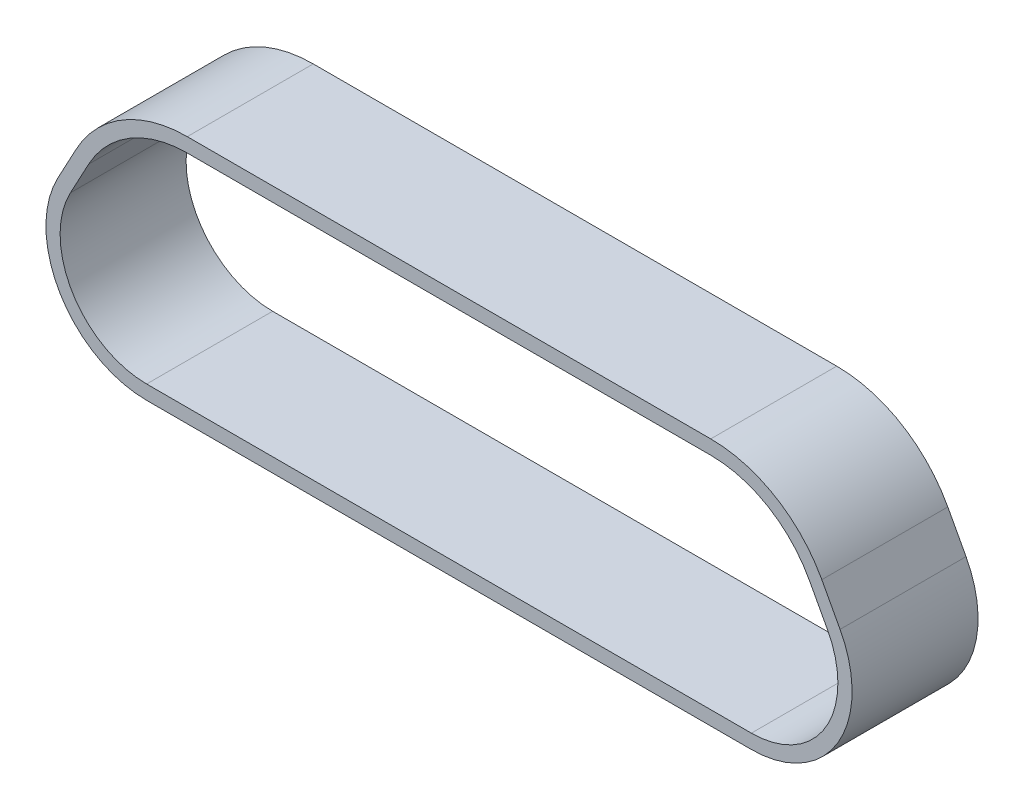
SolidWorks part; units mm, degrees
material "ﾎﾟﾘｳﾚﾀﾝ(POLYURETHANE) (11671)"
ref_plane "正面" through (0, 0, 0) normal (0, 0, 1) x (1, 0, 0)
ref_plane "平面" through (0, 0, 0) normal (0, 1, 0) x (1, 0, 0)
ref_plane "右側面" through (0, 0, 0) normal (1, 0, 0) x (0, 0, -1)
sketch "ｽｹｯﾁ1" plane through (0, 0, 0) normal (0, 0, 1) x (1, 0, 0)
  line L0 (-96, 0) -> (96, 0) construction
  line L2 (-96, -31.83) -> (96, -31.83)
  line L5 (-124.0339, 15.0747) -> (-118.2415, 25.8467)
  line L6 (-83.1, 46.85) -> (83.1, 46.85)
  line L7 (118.2415, 25.8467) -> (124.0339, 15.0747)
  line L8 (121.2536, 27.4664) -> (127.0461, 16.6945) construction
  line L9 (-96, -35.25) -> (96, -35.25) construction
  line L10 (-127.0461, 16.6945) -> (-121.2536, 27.4664) construction
  line L11 (-83.1, 50.27) -> (83.1, 50.27) construction
  line L12 (118.171, 25.8088) -> (123.9635, 15.0369) construction
  line L13 (-96, -31.75) -> (96, -31.75) construction
  line L14 (-123.9635, 15.0369) -> (-118.171, 25.8088) construction
  line L15 (-83.1, 46.77) -> (83.1, 46.77) construction
  arc A0 (-124.0339, 15.0747) -> (-96, -31.83) centre (-96, 0) ccw
  arc A1 (96, -31.83) -> (124.0339, 15.0747) centre (96, 0) ccw
  arc A3 (-118.2415, 25.8467) -> (-83.1, 46.85) centre (-83.1, 6.95) cw
  arc A4 (83.1, 46.85) -> (118.2415, 25.8467) centre (83.1, 6.95) cw
  arc A5 (96, -35.25) -> (127.0461, 16.6945) centre (96, 0) ccw construction
  arc A6 (-127.0461, 16.6945) -> (-96, -35.25) centre (-96, 0) ccw construction
  arc A7 (-121.2536, 27.4664) -> (-83.1, 50.27) centre (-83.1, 6.95) cw construction
  arc A8 (83.1, 50.27) -> (121.2536, 27.4664) centre (83.1, 6.95) cw construction
  arc A9 (96, -31.75) -> (123.9635, 15.0369) centre (96, 0) ccw construction
  arc A10 (-123.9635, 15.0369) -> (-96, -31.75) centre (-96, 0) ccw construction
  arc A11 (-118.171, 25.8088) -> (-83.1, 46.77) centre (-83.1, 6.95) cw construction
  arc A12 (83.1, 46.77) -> (118.171, 25.8088) centre (83.1, 6.95) cw construction
  point P2 (0, 0)
  dimension "D2" = 31.83
  dimension "D3" = 39.9
  dimension "D1" = 192
  dimension "D4" = 46.85
  dimension "D5" = 166.2
  dimension "D6" = 3.42
  dimension "D7" = 3.5
extrude "押し出し-薄板1" add sketch "ｽｹｯﾁ1" along normal blind 40 thin
